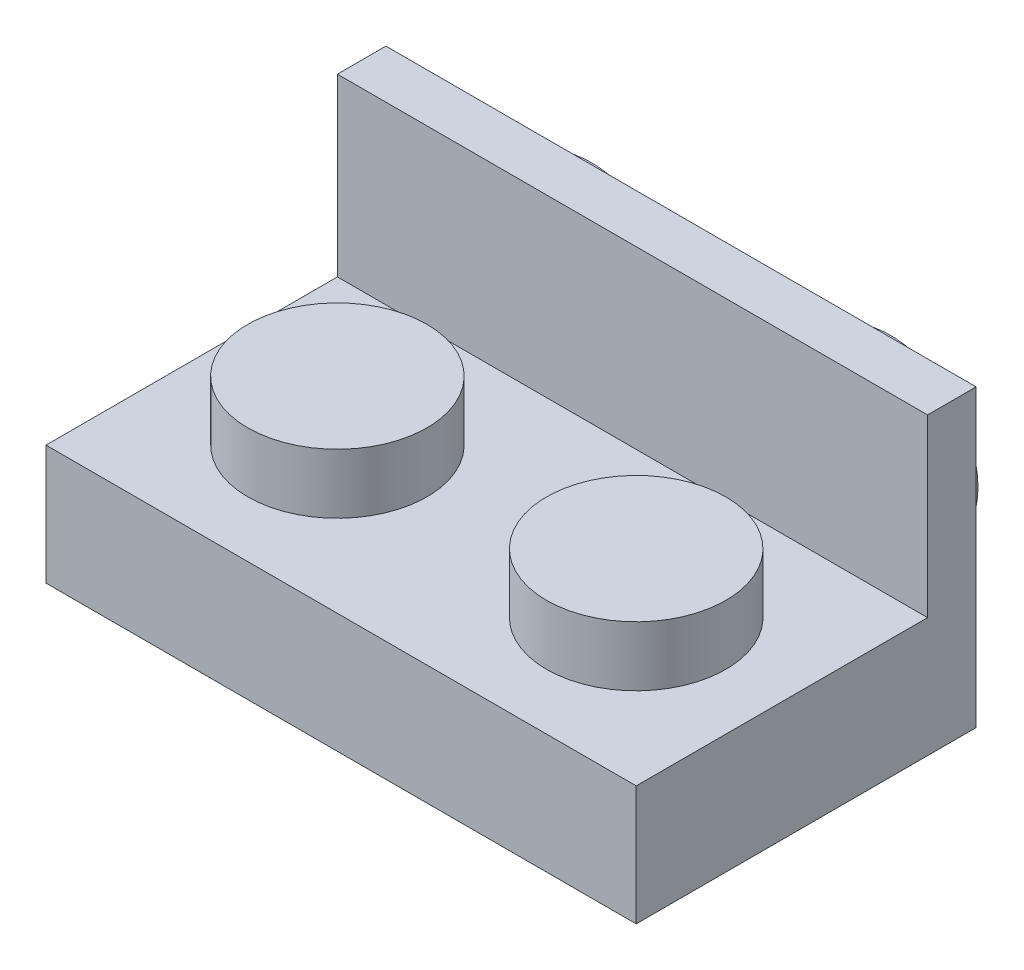
SolidWorks part; units mm, degrees
material "ABS"
ref_plane "Front Plane" through (0, 0, 0) normal (0, 0, 1) x (1, 0, 0)
ref_plane "Top Plane" through (0, 0, 0) normal (0, 1, 0) x (1, 0, 0)
ref_plane "Right Plane" through (0, 0, 0) normal (1, 0, 0) x (0, 0, -1)
sketch "Sketch1" plane through (0, 0, 0) normal (0, 0, 1) x (1, 0, 0)
  line L1 (0, 0) -> (15.8, 0)
  line L2 (0, 0) -> (0, 3.2)
  line L3 (0, 3.2) -> (15.8, 3.2)
  line L4 (15.8, 0) -> (15.8, 3.2)
  line L5 (0, 0) -> (15.8, 3.2) construction
  line L6 (0, 3.2) -> (15.8, 0) construction
  point P4 (7.9, 1.6)
  dimension "D1" = 15.8
  dimension "D2" = 3.2
extrude "Boss-Extrude1" add sketch "Sketch1" against normal blind 7.8
sketch "Sketch2" plane through (0, 3.2, 0) normal (0, 1, 0) x (1, 0, 0)
  line L0 (15.8, 0) -> (0, 0) construction
  circle A0 centre (3.9, 3.9) radius 2.4
  dimension "D1" = 4.8
  dimension "D2" = 3.9
  dimension "D3" = 3.9
extrude "Boss-Extrude2" add sketch "Sketch2" along normal blind 1.6
pattern_linear "LPattern1" count 2 spacing 8 along (0, 0, 1) count 4 spacing 8 along (1, 0, 0) of "Boss-Extrude2"
shell "Shell1" thickness 1.2
sketch "Sketch3" plane through (0, 2, 0) normal (0, -1, 0) x (1, 0, 0)
  line L0 (0, 0) -> (15.8, 0) construction
  line L1 (0, -7.8) -> (0, 0) construction
  circle A0 centre (7.9, -3.9) radius 1.5
  circle A1 centre (7.9, -3.9) radius 0.6
  dimension "D1" = 3
  dimension "D2" = 1.2
  dimension "D3" = 3.9
  dimension "D4" = 7.9
extrude "Boss-Extrude3" add sketch "Sketch3" along normal offset from surface (1.8 mm away) 0.2 up to face at (7.9, 0, -3.9)
sketch "Sketch4" plane through (0, 0, -7.8) normal (0, 0, -1) x (-1, 0, 0)
  line L0 (-15.8, 0) -> (-15.8, 7.9)
  line L1 (-15.8, 7.9) -> (0, 7.9)
  line L2 (0, 7.9) -> (0, 0)
  line L3 (0, 0) -> (-15.8, 0)
  dimension "D1" = 7.9
extrude "Boss-Extrude4" add sketch "Sketch4" along normal blind 1.3
sketch "Sketch5" plane through (0, 0, -9.1) normal (0, 0, -1) x (-1, 0, 0)
  line L0 (0, 7.9) -> (-15.8, 7.9) construction
  line L1 (-15.8, 7.9) -> (-15.8, 0) construction
  circle A0 centre (-11.9, 4) radius 2.35
  circle A1 centre (-11.9, 4) radius 1.65
  dimension "D1" = 4.7
  dimension "D4" = 0.7
  dimension "D2" = 3.9
  dimension "D3" = 3.9
extrude "Boss-Extrude5" add sketch "Sketch5" along normal blind 1.6
pattern_linear "LPattern2" count 2 spacing 8 along (-1, 0, 0) of "Boss-Extrude5"
